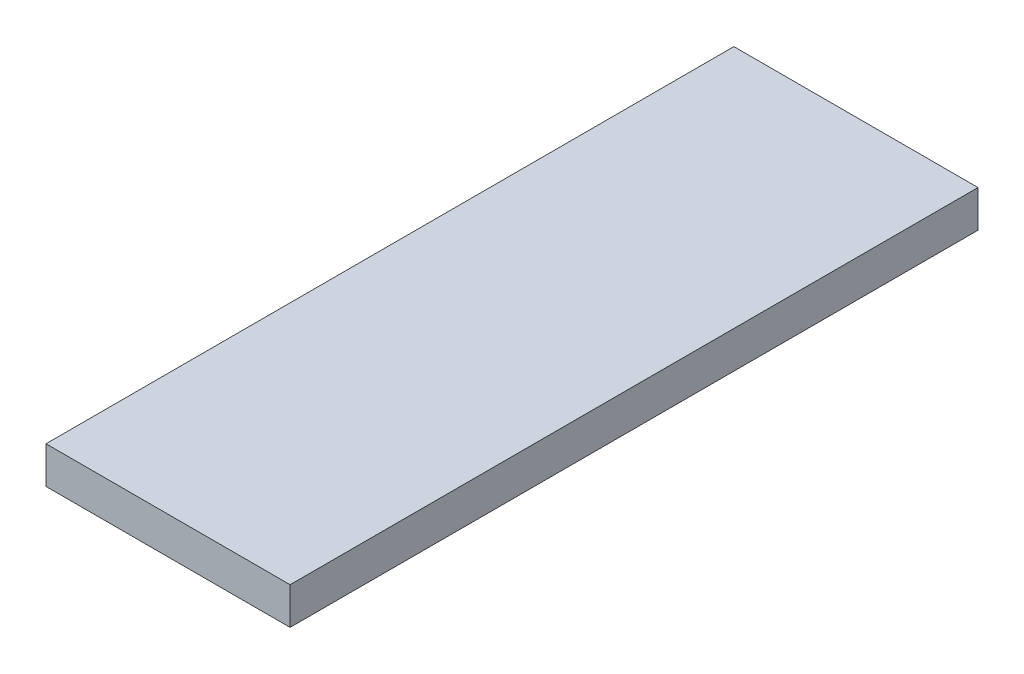
SolidWorks part; units mm, degrees
ref_plane "Plano frontal" through (0, 0, 0) normal (0, 0, 1) x (1, 0, 0)
ref_plane "Plano superior" through (0, 0, 0) normal (0, 1, 0) x (1, 0, 0)
ref_plane "Plano direito" through (0, 0, 0) normal (1, 0, 0) x (0, 0, -1)
sketch "Esboço1" plane through (0, 0, 0) normal (0, 0, 1) x (1, 0, 0)
  line L1 (-33.7162, -13.2117) -> (-0.7162, -13.2117)
  line L2 (-33.7162, -13.2117) -> (-33.7162, -18.2117)
  line L3 (-33.7162, -18.2117) -> (-0.7162, -18.2117)
  line L4 (-0.7162, -13.2117) -> (-0.7162, -18.2117)
extrude "Ressalto-extrusão1" add sketch "Esboço1" along normal blind 93
